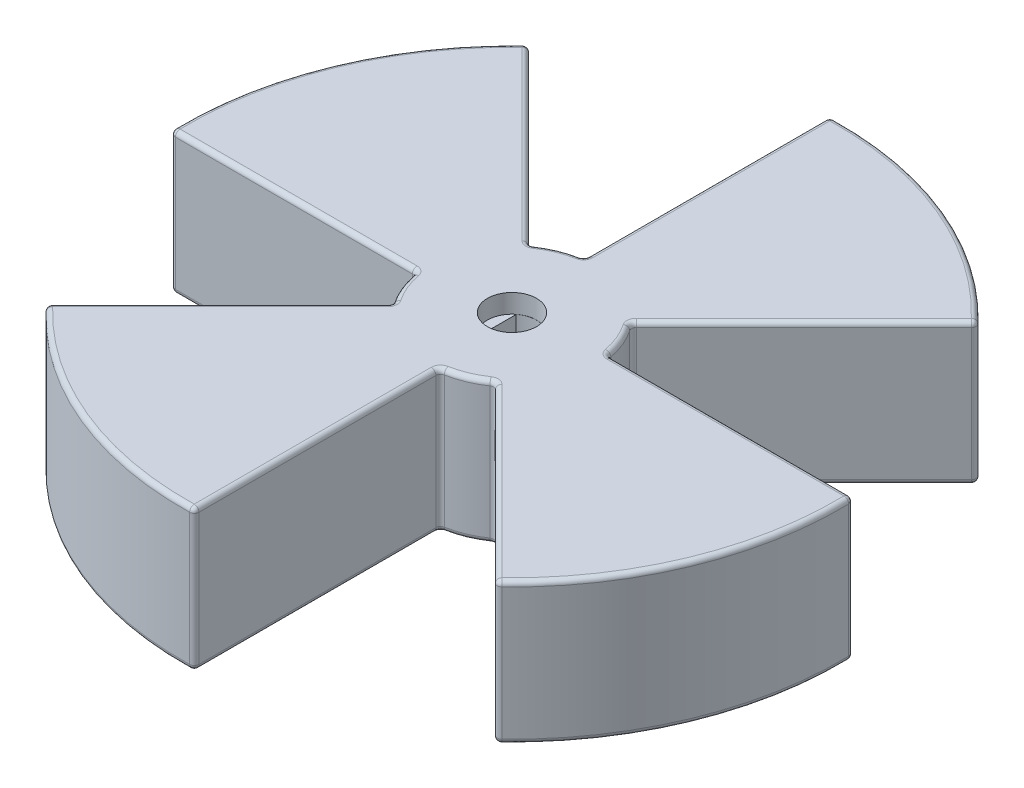
SolidWorks part; units mm, degrees
ref_plane "Front Plane" through (0, 0, 0) normal (0, 0, 1) x (1, 0, 0)
ref_plane "Top Plane" through (0, 0, 0) normal (0, 1, 0) x (1, 0, 0)
ref_plane "Right Plane" through (0, 0, 0) normal (1, 0, 0) x (0, 0, -1)
sketch "Sketch1" plane through (0, 0, 0) normal (0, 1, 0) x (1, 0, 0)
  line L0 (1.6, -2.0494) -> (1.6, 2.0494)
  line L1 (-1.6, -2.0494) -> (-1.6, 2.0494)
  line L2 (1.6, -2.0494) -> (-1.6, -2.0494) construction
  line L3 (1.6, 2.0494) -> (-1.6, 2.0494) construction
  circle A0 centre (0, 0) radius 9
  arc A1 (1.6, 2.0494) -> (-1.6, 2.0494) centre (0, 0) ccw
  arc A2 (-1.6, -2.0494) -> (1.6, -2.0494) centre (0, 0) ccw
  dimension "D1" = 18
  dimension "D2" = 5.2
  dimension "D3" = 3.2
extrude "Boss-Extrude1" add sketch "Sketch1" along normal blind 15
sketch "Sketch4" plane through (0, 0, 0) normal (0, 1, 0) x (1, 0, 0)
  line L0 (35, 0) -> (8, 0) construction
  line L2 (8, -1.25) -> (35, -1.25)
  line L3 (8, -1.25) -> (8, 1.25)
  line L4 (8, 1.25) -> (35, 1.25)
  line L5 (35, -1.25) -> (35, 1.25)
  dimension "D1" = 0
  dimension "D2" = 8
  dimension "D3" = 2.5
  dimension "D4" = 35
extrude "Boss-Extrude2" add sketch "Sketch4" along normal up to surface (15 mm away) up to face at (0, 15, 9)
pattern_circular "CirPattern1" count 8 over 360 about axis through (0, 0, 0) along (0, 1, 0) of "Boss-Extrude2"
sketch "Sketch6" plane through (0, 15, 0) normal (0, 1, 0) x (1, 0, 0)
  circle A0 centre (0, 0) radius 2.61
  dimension "D1" = 5.22
extrude "Cut-Extrude2" cut sketch "Sketch6" against normal blind 2
sketch "Sketch7" plane through (0, 0, 0) normal (0, 1, 0) x (1, 0, 0)
  line L0 (1.25, 35) -> (-1.25, 35) construction
  line L1 (-1.25, 35) -> (-0.2498, 6.9955)
  line L2 (5.1233, 4.7699) -> (25.6326, 23.8649)
  line L3 (-0.2498, 6.9955) -> (0, 0) construction
  line L4 (0, 0) -> (5.1233, 4.7699) construction
  arc A0 (25.6326, 23.8649) -> (-1.25, 35) centre (0, 0) ccw
  arc A1 (5.1233, 4.7699) -> (-0.2498, 6.9955) centre (0, 0) ccw
  dimension "D1" = 14
  dimension "D2" = 28.0223
  dimension "D3" = 28.0045
extrude "Boss-Extrude3" add sketch "Sketch7" along normal up to surface (15 mm away) up to face at (0, 15, 2.61)
pattern_circular "CirPattern2" count 4 over 360 about axis through (0, 15, 0) along (0, 1, 0) of "Boss-Extrude3"
fillet "Fillet1" radius 0.5 48 edges at (-21.9564, 15, 1.25) (-7.1862, 7.5, 5.4184) (-16.4094, 0, 14.6416) (-25.6326, 7.5, 23.8649) (-16.4094, 15, 14.6416) (3.4442, 0, 8.3149) (3.4442, 15, 8.3149) (1.25, 0, 21.9564) (1.25, 7.5, 8.9128) (1.25, 7.5, 35) (1.25, 15, 21.9564) (5.4184, 7.5, 7.1862) (14.6416, 0, 16.4094) (23.8649, 7.5, 25.6326) (14.6416, 15, 16.4094) (13.4025, 0, -32.3564) (13.4025, 15, -32.3564) (8.3149, 15, -3.4442) (8.3149, 0, -3.4442) (8.9128, 7.5, -1.25) (-32.3564, 0, -13.4025) (-32.3564, 15, -13.4025) (-13.4025, 0, 32.3564) (-13.4025, 15, 32.3564) (21.9564, 0, -1.25) (35, 7.5, -1.25) (32.3564, 0, 13.4025) (32.3564, 15, 13.4025) (21.9564, 15, -1.25) (7.1862, 7.5, -5.4184) (16.4094, 0, -14.6416) (25.6326, 7.5, -23.8649) (16.4094, 15, -14.6416) (-3.4442, 0, -8.3149) (-3.4442, 15, -8.3149) (-1.25, 0, -21.9564) (-1.25, 7.5, -8.9128) (-1.25, 7.5, -35) (-1.25, 15, -21.9564) (-5.4184, 7.5, -7.1862) (-14.6416, 0, -16.4094) (-23.8649, 7.5, -25.6326) (-14.6416, 15, -16.4094) (-8.3149, 0, 3.4442) (-8.3149, 15, 3.4442) (-21.9564, 0, 1.25) (-8.9128, 7.5, 1.25) (-35, 7.5, 1.25)
sketch "Sketch8" plane through (0, 0, 0) normal (0, 1, 0) x (1, 0, 0)
  line L5 (23.8636, -22.0959) -> (7.4864, -5.7187)
  line L6 (9.3374, -1.25) -> (32.4983, -1.25)
  line L7 (23.8636, -22.0959) -> (7.5589, -5.7911)
  line L8 (9.4399, -1.25) -> (32.4983, -1.25)
  arc A4 (23.8636, -22.0959) -> (32.4983, -1.25) centre (0, 0) ccw
  arc A5 (23.8636, -22.0959) -> (32.4983, -1.25) centre (0, 0) ccw
  arc A7 (6.5854, -6.878) -> (9.5201, 0.2069) centre (0, 0) ccw
  arc A8 (7.5589, -5.7911) -> (9.4399, -1.25) centre (0, 0) ccw
  dimension "D1" = 2
  dimension "D2" = 25
extrude "Cut-Extrude3" cut sketch "Sketch8" along normal blind 13
pattern_circular "CirPattern3" count 4 over 360 about axis through (0, 0, 0) along (0, 1, 0) of "Cut-Extrude3"
sketch "Sketch9" plane through (0, 0, 0) normal (0, 1, 0) x (1, 0, 0)
  circle A0 centre (0, 0) radius 2.6024
  dimension "D1" = 5.2048
extrude "Cut-Extrude4" cut sketch "Sketch9" along normal blind 3
